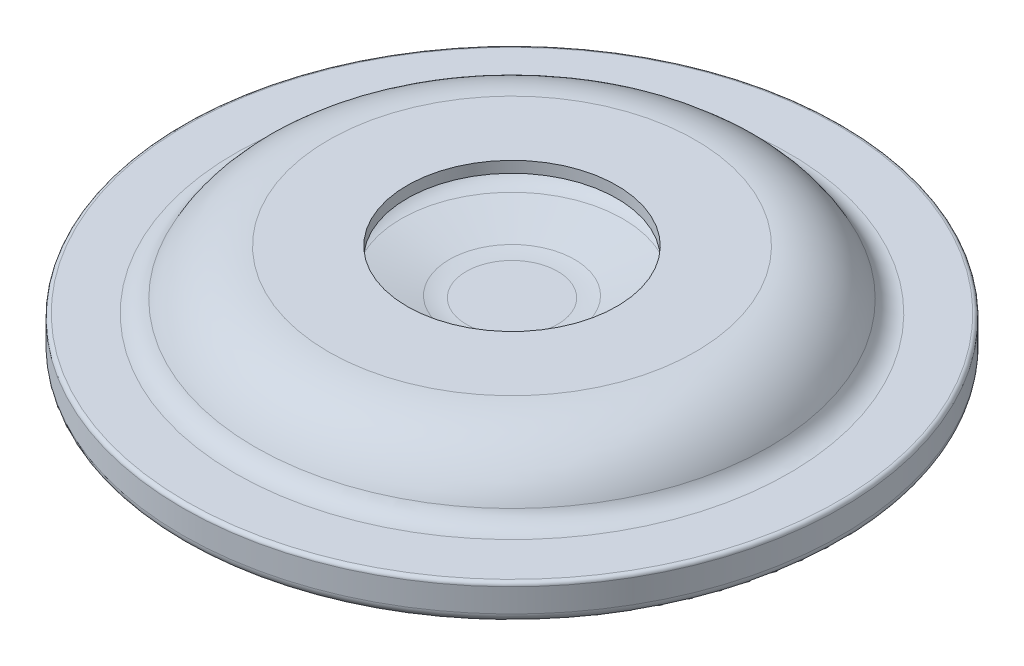
SolidWorks part; units mm, degrees
material "Nitrile Rubber"
ref_plane "Front Plane" through (0, 0, 0) normal (0, 0, 1) x (1, 0, 0)
ref_plane "Top Plane" through (0, 0, 0) normal (0, 1, 0) x (1, 0, 0)
ref_plane "Right Plane" through (0, 0, 0) normal (1, 0, 0) x (0, 0, -1)
sketch "Sketch2" plane through (0, 0, 0) normal (0, 0, 1) x (1, 0, 0)
  line L0 (14, 6) -> (24.5, 6)
  line L1 (9.5612, -1.332) -> (12.5454, -0.7536)
  line L2 (8.3602, 0.2563) -> (14.8, 1.7431) construction
  line L3 (14, 4.5) -> (15.75, 4.5) construction
  line L4 (36.99, -1.8) -> (43.5, -1.8)
  line L5 (39.5, -6.7) -> (42.75, -6.7)
  line L6 (44, -2.3) -> (44, -5.45)
  line L7 (40.6737, -6.7) -> (0, -6.7) construction
  line L8 (39, -6.2) -> (39, -4.55)
  line L9 (37.75, -3.3) -> (36.7343, -3.3)
  line L13 (8.3602, 0.2563) -> (14.8, 1.7431)
  line L14 (14, 4.5) -> (15.75, 4.5)
  line L16 (6.1106, 0) -> (0, 0)
  line L17 (0, 0) -> (0, -2.25)
  line L18 (0, 0) -> (0, -23.4246) construction
  line L25 (14, 4.5) -> (14, 6) construction
  line L27 (14, 4.5) -> (14, 6)
  arc A0 (6.1106, 0) -> (8.3602, 0.2563) centre (6.1106, 10) ccw construction
  arc A2 (34.2943, -0.1165) -> (24.5, 6) centre (24.5, -4.9) ccw
  arc A3 (25.4706, 4.3487) -> (21.8305, 4.245) centre (23.8799, -3.7552) ccw
  arc A4 (36.99, -1.8) -> (34.2943, -0.1165) centre (36.99, 1.2) cw
  arc A5 (32.7996, -0.9836) -> (36.7343, -3.3) centre (36.7343, 1.2) ccw
  arc A6 (44, -5.45) -> (42.75, -6.7) centre (42.75, -5.45) cw
  arc A7 (6.1106, 0) -> (8.3602, 0.2563) centre (6.1106, 10) ccw
  arc A8 (43.5, -1.8) -> (44, -2.3) centre (43.5, -2.3) cw
  arc A9 (39, -4.55) -> (37.75, -3.3) centre (37.75, -4.55) ccw
  arc A10 (15.9728, 0.5474) -> (17.1678, 1.5011) centre (13.1728, 5.2813) ccw
  arc A11 (39, -6.2) -> (39.5, -6.7) centre (39.5, -6.2) ccw
  arc A12 (16.5624, 2.9169) -> (15.75, 4.5) centre (15.75, 3.5) ccw construction
  arc A13 (14.8, 1.7431) -> (16.5624, 2.9169) centre (14.1252, 4.6662) ccw construction
  arc A14 (16.5624, 2.9169) -> (15.75, 4.5) centre (15.75, 3.5) ccw
  arc A15 (14.8, 1.7431) -> (16.5624, 2.9169) centre (14.1252, 4.6662) ccw
  arc A16 (9.5612, -1.332) -> (0, -2.25) centre (0, 48) cw
  arc A17 (15.9728, 0.5474) -> (12.5454, -0.7536) centre (10.5, 9.8) cw
  arc A18 (32.7996, -0.9836) -> (25.4706, 4.3487) centre (23.4, -6.2) ccw
  arc A19 (21.8305, 4.245) -> (17.1678, 1.5011) centre (24.25, -5.2) ccw
  point P20 (23.6448, 4.5)
  point P28 (7.5, 0.0577)
  point P41 (37.2421, -3.3)
  dimension "D9" = 50.25
  dimension "D13" = 24.5
  dimension "D16" = 24.25
  dimension "D19" = 0.5
  dimension "D21" = 1.5
  dimension "D5" = 1.25
  dimension "D18" = 4.9
  dimension "D7" = 1.25
  dimension "D24" = 10.9
  dimension "D25" = 3
  dimension "D27" = 15
  dimension "D12" = 0.5
  dimension "D30" = 10.5
  dimension "D32" = 23.4
  dimension "D34" = 10.75
  dimension "D33" = 0.5
  dimension "D23" = 4.5
  dimension "D26" = 54.7
  dimension "D15" = 1.5
  dimension "D22" = 5.5
  dimension "D29" = 16.5
  dimension "D10" = 10.75
  dimension "D11" = 9.75
  dimension "D17" = 3.1
  dimension "D3" = 88
  dimension "D4" = 78
  dimension "D6" = 1.5
  dimension "D8" = 12.7
  dimension "D20" = 3.4
revolve "Revolve1" add sketch "Sketch2" angle 360 about L18
